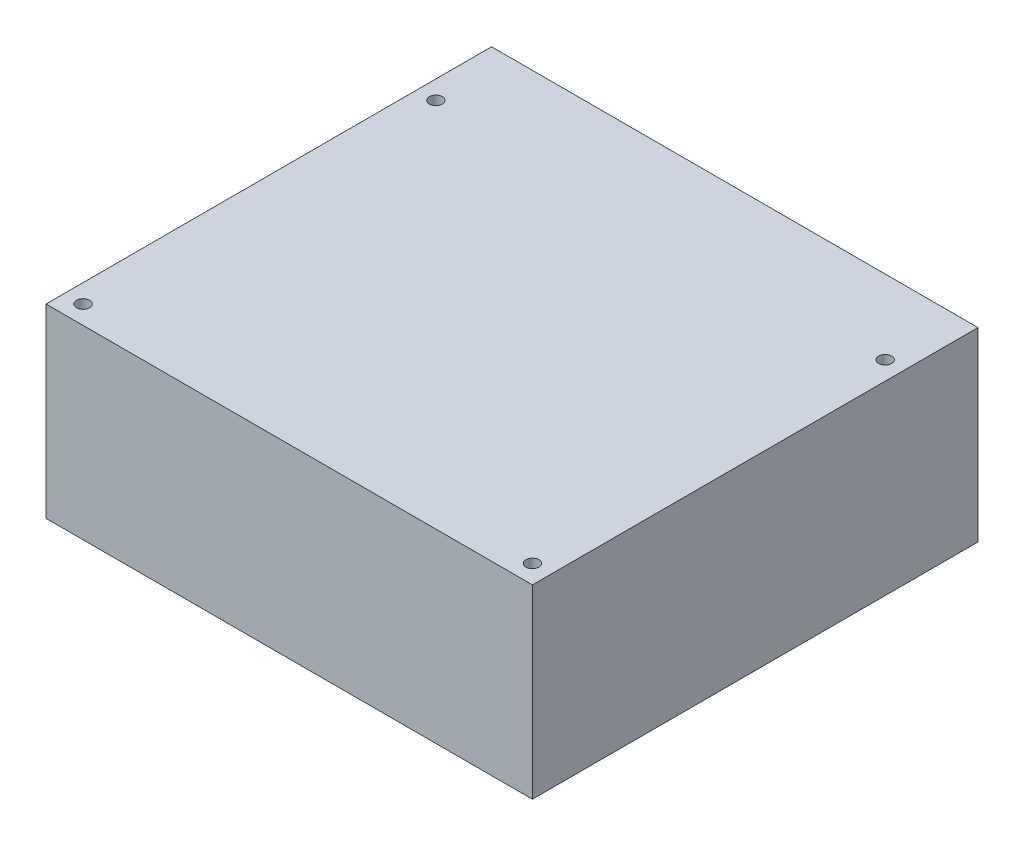
SolidWorks part; units mm, degrees
ref_plane "Front Plane" through (0, 0, 0) normal (0, 0, 1) x (1, 0, 0)
ref_plane "Top Plane" through (0, 0, 0) normal (0, 1, 0) x (1, 0, 0)
ref_plane "Right Plane" through (0, 0, 0) normal (1, 0, 0) x (0, 0, -1)
sketch "Sketch1" plane through (0, 0, 0) normal (0, 1, 0) x (1, 0, 0)
  line L0 (-85.4, -55) -> (103.1714, -55) construction
  line L1 (-65.5, 60) -> (65.5, 60)
  line L2 (-65.5, 60) -> (-65.5, -60)
  line L3 (-65.5, -60) -> (65.5, -60)
  line L4 (65.5, 60) -> (65.5, -60)
  line L5 (-65.5, 60) -> (65.5, -60) construction
  line L6 (-65.5, -60) -> (65.5, 60) construction
  line L7 (-85.4, 40) -> (103.1714, 40) construction
  line L8 (-60.5, -78.3389) -> (-60.5, 69.7674) construction
  line L9 (60.5, -78.3389) -> (60.5, 69.7674) construction
  circle A0 centre (-60.5, -55) radius 1.75
  circle A1 centre (60.5, -55) radius 1.75
  circle A2 centre (60.5, 40) radius 1.75
  circle A3 centre (-60.5, 40) radius 1.75
  point P0 (0, 0)
  dimension "D7" = 3.5
  dimension "D1" = 120
  dimension "D2" = 131
  dimension "D3" = 5
  dimension "D4" = 5
  dimension "D5" = 5
  dimension "D6" = 95
extrude "Boss-Extrude1" add sketch "Sketch1" along normal blind 50
